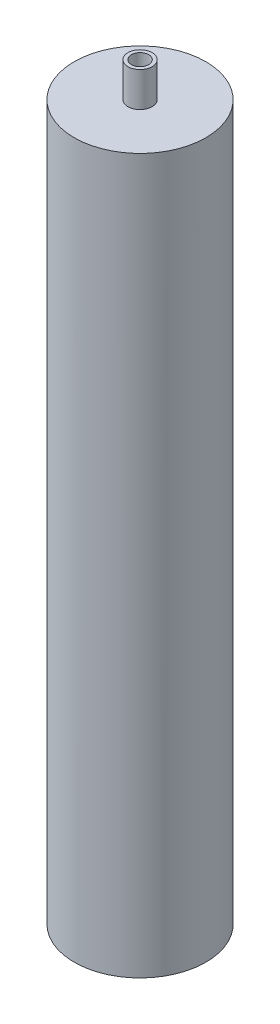
SolidWorks part; units mm, degrees
material "ABS"
ref_plane "前视基准面" through (0, 0, 0) normal (0, 0, 1) x (1, 0, 0)
ref_plane "上视基准面" through (0, 0, 0) normal (0, 1, 0) x (1, 0, 0)
ref_plane "右视基准面" through (0, 0, 0) normal (1, 0, 0) x (0, 0, -1)
sketch "草图1" plane through (0, 0, 0) normal (0, 1, 0) x (1, 0, 0)
  circle A0 centre (0, 0) radius 19
  circle A1 centre (0, 0) radius 18
  dimension "D1" = 38
  dimension "D2" = 36
extrude "凸台-拉伸1" add sketch "草图1" along normal blind 150
sketch "草图2" plane through (0, 150, 0) normal (0, 1, 0) x (1, 0, 0)
  line L5 (0, 10) -> (0, 15.61)
  line L6 (0, 15.61) -> (6.2, 15.61)
  line L7 (6.2, 15.61) -> (6.2, 9.89)
  line L8 (6.2, 9.89) -> (0, 9.89)
  line L9 (0, 9.89) -> (0, 10)
  circle A0 centre (0, 0) radius 19
  circle A2 centre (0, 0) radius 10 construction
  circle A3 centre (0, 10) radius 2 construction
  circle A4 centre (10, 0) radius 2
  circle A5 centre (-10, 0) radius 2
  circle A6 centre (0, -10) radius 2
  circle A7 centre (0, 0) radius 2.5
  dimension "D1" = 38
  dimension "D2" = 20
  dimension "D3" = 4
  dimension "D4" = 4
  dimension "D5" = 4
  dimension "D6" = 4
  dimension "D7" = 5
  dimension "D8" = 5.61
  dimension "D9" = 6.2
  dimension "D10" = 5.72
extrude "凸台-拉伸2" add sketch "草图2" along normal blind 2
sketch "草图3" plane through (0, 152, 0) normal (0, 1, 0) x (1, 0, 0)
  circle A0 centre (0, 0) radius 19
  circle A1 centre (0, 0) radius 18
  dimension "D1" = 38
  dimension "D2" = 36
extrude "凸台-拉伸3" add sketch "草图3" along normal blind 50
sketch "草图4" plane through (0, 202, 0) normal (0, 1, 0) x (1, 0, 0)
  circle A0 centre (0, 0) radius 19
  circle A1 centre (0, 0) radius 2.5
  dimension "D1" = 38
  dimension "D2" = 5
extrude "凸台-拉伸4" add sketch "草图4" along normal blind 2
sketch "草图5" plane through (0, 204, 0) normal (0, 1, 0) x (1, 0, 0)
  circle A0 centre (0, 0) radius 2.5
  circle A1 centre (0, 0) radius 3.5
  dimension "D1" = 5
  dimension "D2" = 7
extrude "凸台-拉伸5" add sketch "草图5" along normal blind 10
sketch "草图6" plane through (0, 0, 0) normal (0, -1, 0) x (1, 0, 0)
  circle A0 centre (0, 0) radius 19
  circle A1 centre (0, 0) radius 12.5
  dimension "D1" = 38
  dimension "D2" = 25
extrude "凸台-拉伸6" add sketch "草图6" along normal blind 2
